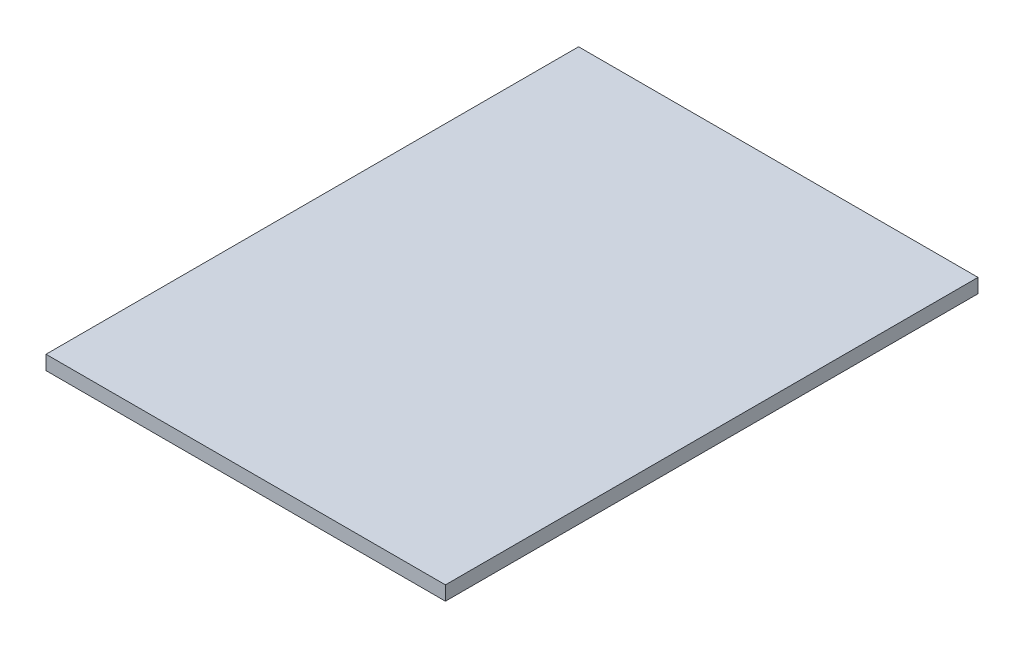
SolidWorks part; units mm, degrees
ref_plane "Front Plane" through (0, 0, 0) normal (0, 0, 1) x (1, 0, 0)
ref_plane "Top Plane" through (0, 0, 0) normal (0, 1, 0) x (1, 0, 0)
ref_plane "Right Plane" through (0, 0, 0) normal (1, 0, 0) x (0, 0, -1)
sketch "Sketch1" plane through (0, 0, 0) normal (0, 1, 0) x (1, 0, 0)
  line L1 (-225, -300) -> (225, -300)
  line L2 (-225, -300) -> (-225, 300)
  line L3 (-225, 300) -> (225, 300)
  line L4 (225, -300) -> (225, 300)
  line L5 (-225, -300) -> (225, 300) construction
  line L6 (-225, 300) -> (225, -300) construction
  point P0 (0, 0)
  dimension "D1" = 600
  dimension "D2" = 450
extrude "Boss-Extrude1" add sketch "Sketch1" along normal blind 16 contours L2 L3 L4 L1
